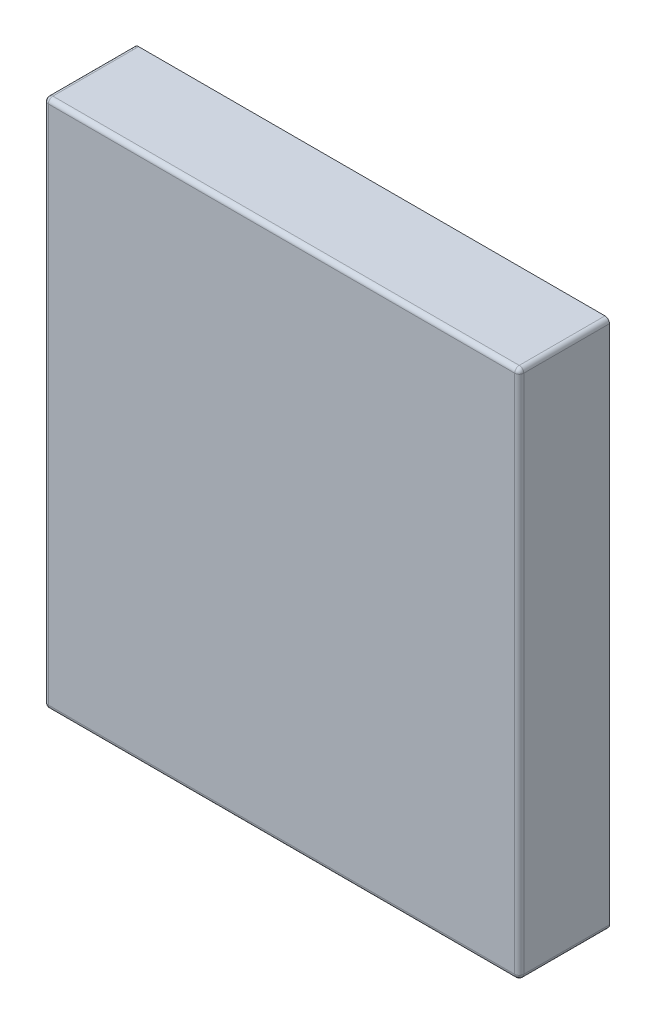
SolidWorks part; units mm, degrees
ref_plane "Plano frontal" through (0, 0, 0) normal (0, 0, 1) x (1, 0, 0)
ref_plane "Plano superior" through (0, 0, 0) normal (0, 1, 0) x (1, 0, 0)
ref_plane "Plano direito" through (0, 0, 0) normal (1, 0, 0) x (0, 0, -1)
sketch "Esboço1" plane through (0, 0, 0) normal (0, 0, 1) x (1, 0, 0)
  line L5 (7.9, -8.8) -> (-7.9, -8.8)
  line L6 (7.9, -8.8) -> (7.9, 8.8)
  line L11 (7.9, 8.8) -> (-7.9, 8.8)
  line L12 (-7.9, -8.8) -> (-7.9, 8.8)
  line L13 (7.9, -8.8) -> (-7.9, 8.8) construction
  line L14 (7.9, 8.8) -> (-7.9, -8.8) construction
  point P0 (0, 0)
  dimension "D1" = 17.6
  dimension "D2" = 15.8
extrude "Ressalto-extrusão1" add sketch "Esboço1" along normal mid plane 3
fillet "Filete1" radius 0.15 8 edges at (-7.9, -8.8, 0) (7.9, -8.8, 0) (7.9, 8.8, 0) (-7.9, 8.8, 0) (7.9, 0, 1.5) (0, -8.8, 1.5) (-7.9, 0, 1.5) (0, 8.8, 1.5)
